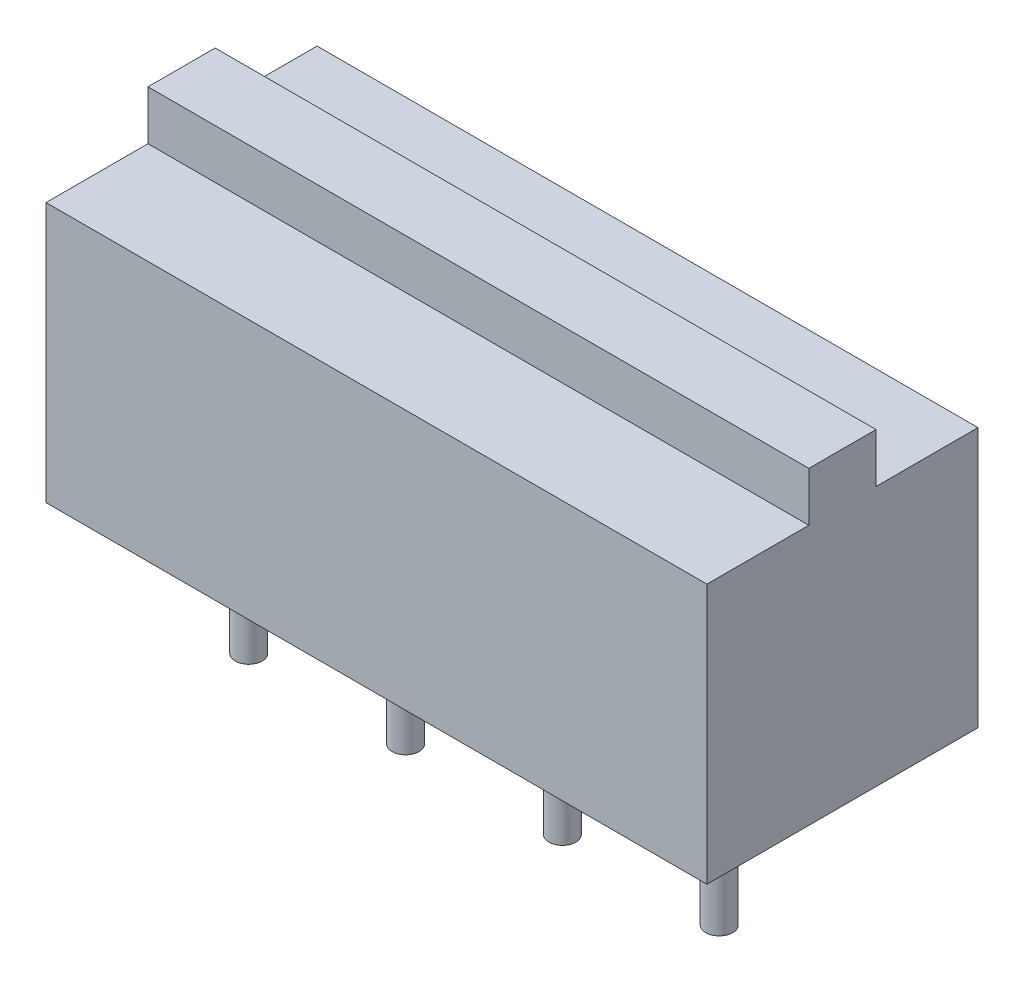
SolidWorks part; units mm, degrees
ref_plane "Alzado" through (0, 0, 0) normal (0, 0, 1) x (1, 0, 0)
ref_plane "Planta" through (0, 0, 0) normal (0, 1, 0) x (1, 0, 0)
ref_plane "Vista lateral" through (0, 0, 0) normal (1, 0, 0) x (0, 0, -1)
sketch "Croquis1" plane through (0, 0, 0) normal (0, 1, 0) x (1, 0, 0)
  line L1 (-14.75, -6.05) -> (14.75, -6.05)
  line L2 (-14.75, -6.05) -> (-14.75, 6.05)
  line L3 (-14.75, 6.05) -> (14.75, 6.05)
  line L4 (14.75, -6.05) -> (14.75, 6.05)
  line L5 (-14.75, -6.05) -> (14.75, 6.05) construction
  line L6 (-14.75, 6.05) -> (14.75, -6.05) construction
  point P0 (0, 0)
  dimension "D1" = 29.5
  dimension "D2" = 12.1
extrude "Saliente-Extruir1" add sketch "Croquis1" along normal blind 11.6
sketch "Croquis2" plane through (0, 11.6, 0) normal (0, 1, 0) x (1, 0, 0)
  line L0 (14.75, -6.05) -> (14.75, 6.05) construction
  line L1 (-14.75, -1.5) -> (14.75, -1.5)
  line L2 (-14.75, -1.5) -> (-14.75, 1.5)
  line L3 (-14.75, 1.5) -> (14.75, 1.5)
  line L4 (14.75, -1.5) -> (14.75, 1.5)
  line L5 (-14.75, -1.5) -> (14.75, 1.5) construction
  line L6 (-14.75, 1.5) -> (14.75, -1.5) construction
  point P0 (0, 0)
  dimension "D1" = 3
extrude "Saliente-Extruir2" add sketch "Croquis2" along normal blind 2.2
sketch "Croquis3" plane through (0, 0, 0) normal (0, -1, 0) x (1, 0, 0)
  line L0 (-14.75, -6.05) -> (-14.75, 6.05) construction
  line L1 (-14.75, 6.05) -> (14.75, 6.05) construction
  circle A0 centre (-11.5, -1.35) radius 0.6
  circle A1 centre (-8, 3.75) radius 0.6
  circle A5 centre (-4.5, -1.35) radius 0.6
  circle A6 centre (-1, 3.75) radius 0.6
  circle A7 centre (2.5, -1.35) radius 0.6
  circle A8 centre (6, 3.75) radius 0.6
  circle A9 centre (9.5, -1.35) radius 0.6
  circle A10 centre (13, 3.75) radius 0.6
  dimension "D1" = 3.25
  dimension "D2" = 3.5
  dimension "D3" = 2.3
  dimension "D4" = 5.1
  dimension "D5" = 1.2
  dimension "D7" = 7
  dimension "D6" = 4
extrude "Saliente-Extruir3" add sketch "Croquis3" along normal blind 3.6
